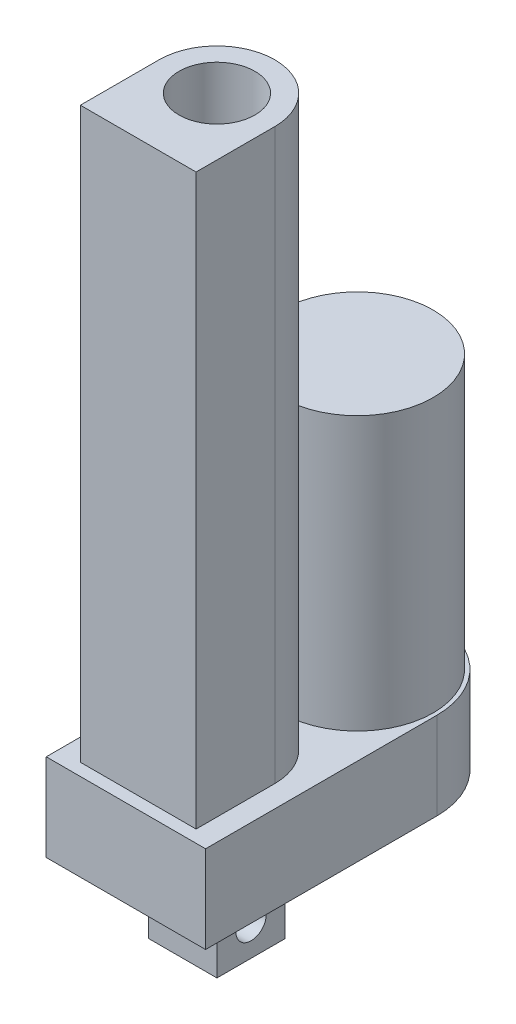
SolidWorks part; units mm, degrees
ref_plane "Front Plane" through (0, 0, 0) normal (0, 0, 1) x (1, 0, 0)
ref_plane "Top Plane" through (0, 0, 0) normal (0, 1, 0) x (1, 0, 0)
ref_plane "Right Plane" through (0, 0, 0) normal (1, 0, 0) x (0, 0, -1)
sketch "Sketch1" plane through (0, 0, 0) normal (0, 1, 0) x (1, 0, 0)
  line L0 (0, 0) -> (0, -24) construction
  line L1 (-21, -24) -> (21, -24)
  line L2 (21, -24) -> (21, 37)
  line L3 (-21, -24) -> (-21, 37)
  arc A0 (21, 37) -> (-21, 37) centre (0, 37) ccw
  point P7 (0, 0)
  point P8 (0, 0)
  dimension "D1" = 24
  dimension "D2" = 21
extrude "Boss-Extrude1" add sketch "Sketch1" against normal blind 23
sketch "Sketch2" plane through (0, -23, 0) normal (0, -1, 0) x (1, 0, 0)
  line L1 (-9, 9) -> (9, 9)
  line L2 (-9, 9) -> (-9, -9)
  line L3 (-9, -9) -> (9, -9)
  line L4 (9, 9) -> (9, -9)
  line L5 (-9, 9) -> (9, -9) construction
  line L6 (-9, -9) -> (9, 9) construction
  point P0 (0, 0)
  dimension "D1" = 18
extrude "Boss-Extrude2" add sketch "Sketch2" along normal blind 20
sketch "Sketch3" plane through (0, 0, 0) normal (1, 0, 0) x (0, 0, -1)
  line L0 (0, -23) -> (0, -35) construction
  line L1 (9, -23) -> (-9, -23) construction
  circle A0 centre (0, -35) radius 4
  dimension "D2" = 8
  dimension "D1" = 12
extrude "Cut-Extrude1" cut sketch "Sketch3" against normal through all both and the other way through all
sketch "Sketch4" plane through (0, -23, 0) normal (0, -1, 0) x (1, 0, 0)
  circle A0 centre (0, -37) radius 20
  dimension "D1" = 40
extrude "Boss-Extrude3" add sketch "Sketch4" against normal blind 95
sketch "Sketch5" plane through (0, 0, 0) normal (0, 1, 0) x (1, 0, 0)
  line L0 (-15.25, 0) -> (-15.25, -20.75)
  line L1 (-15.25, -20.75) -> (15.25, -20.75)
  line L2 (15.25, -20.75) -> (15.25, 0)
  arc A0 (15.25, 0) -> (-15.25, 0) centre (0, 0) ccw
  circle A1 centre (0, 0) radius 10
  point P6 (7.0172, -2.7694)
  dimension "D1" = 30.5
  dimension "D2" = 20
  dimension "D3" = 20.75
extrude "Boss-Extrude4" add sketch "Sketch5" along normal blind 150
